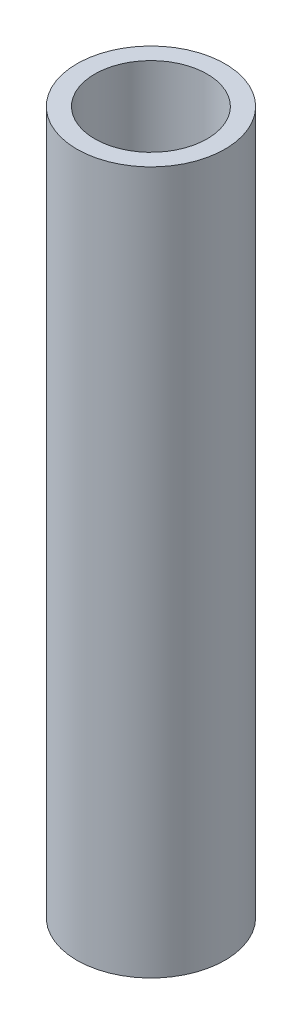
SolidWorks part; units mm, degrees
ref_plane "Front Plane" through (0, 0, 0) normal (0, 0, 1) x (1, 0, 0)
ref_plane "Top Plane" through (0, 0, 0) normal (0, 1, 0) x (1, 0, 0)
ref_plane "Right Plane" through (0, 0, 0) normal (1, 0, 0) x (0, 0, -1)
sketch "Sketch1" plane through (0, 0, 0) normal (0, 1, 0) x (1, 0, 0)
  circle A0 centre (0, 0) radius 1.054
  circle A1 centre (0, 0) radius 0.8
extrude "Boss-Extrude1" add sketch "Sketch1" along normal blind 10
